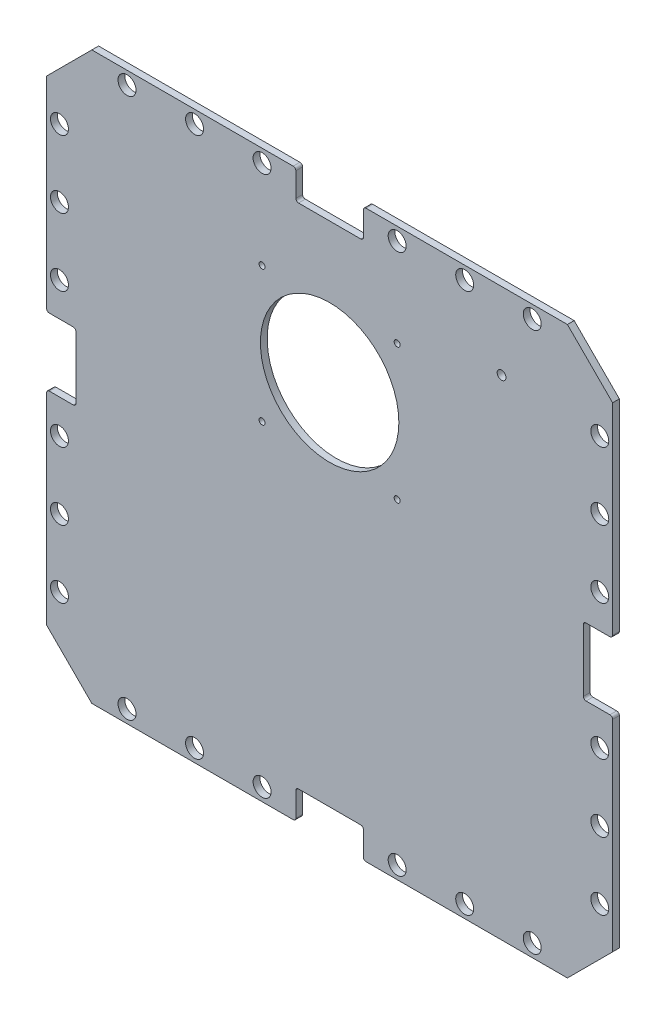
SolidWorks part; units mm, degrees
ref_plane "Front Plane" through (0, 0, 0) normal (0, 0, 1) x (1, 0, 0)
ref_plane "Top Plane" through (0, 0, 0) normal (0, 1, 0) x (1, 0, 0)
ref_plane "Right Plane" through (0, 0, 0) normal (1, 0, 0) x (0, 0, -1)
sketch "Sketch1" plane through (0, 0, 0) normal (0, 0, 1) x (1, 0, 0)
  line L0 (30.226, -4.826) -> (55.626, -4.826) construction
  line L1 (0, 0) -> (212.852, 0)
  line L2 (0, 0) -> (0, -212.852)
  line L3 (0, -212.852) -> (212.852, -212.852)
  line L4 (212.852, 0) -> (212.852, -212.852)
  line L5 (55.626, -4.826) -> (81.026, -4.826) construction
  line L6 (81.026, -4.826) -> (106.426, -4.826) construction
  line L7 (106.426, -4.826) -> (131.826, -4.826) construction
  line L8 (131.826, -4.826) -> (157.226, -4.826) construction
  line L9 (157.226, -4.826) -> (182.626, -4.826) construction
  line L10 (106.426, 0) -> (106.426, -212.852) construction
  line L11 (0, -106.426) -> (212.852, -106.426) construction
  line L12 (16.9978, 0) -> (0, -16.9978)
  line L13 (212.852, -16.9978) -> (195.8542, 0)
  line L14 (195.8542, -212.852) -> (212.852, -195.8542)
  line L15 (0, -195.8542) -> (16.9978, -212.852)
  line L16 (93.726, 0) -> (93.726, -11)
  line L17 (81.026, -38.2041) -> (131.826, -38.2042) construction
  line L18 (81.026, -38.2041) -> (81.026, -89.0042) construction
  line L19 (81.026, -89.0042) -> (131.826, -89.0042) construction
  line L20 (131.826, -38.2042) -> (131.826, -89.0042) construction
  line L21 (106.426, -89.0042) -> (106.426, -38.2041) construction
  line L22 (81.026, -63.6041) -> (131.826, -63.6041) construction
  line L23 (93.726, -11) -> (119.126, -11)
  line L24 (119.126, -11) -> (119.126, 0)
  line L25 (212.852, -93.726) -> (201.852, -93.726)
  line L26 (201.852, -93.726) -> (201.852, -119.126)
  line L27 (201.852, -119.126) -> (212.852, -119.126)
  line L28 (119.126, -212.852) -> (119.126, -201.852)
  line L29 (119.126, -201.852) -> (93.726, -201.852)
  line L30 (93.726, -201.852) -> (93.726, -212.852)
  line L31 (0, -119.126) -> (11, -119.126)
  line L32 (11, -119.126) -> (11, -93.726)
  line L33 (11, -93.726) -> (0, -93.726)
  circle A0 centre (30.226, -4.826) radius 3.38
  circle A1 centre (55.626, -4.826) radius 3.38
  circle A2 centre (81.026, -4.826) radius 3.38
  circle A3 centre (131.826, -4.826) radius 3.38
  circle A4 centre (157.226, -4.826) radius 3.38
  circle A5 centre (182.626, -4.826) radius 3.38
  circle A6 centre (106.426, -4.826) radius 5.1943
  circle A7 centre (208.026, -182.626) radius 3.38
  circle A8 centre (208.026, -157.226) radius 3.38
  circle A9 centre (208.026, -131.826) radius 3.38
  circle A10 centre (208.026, -106.426) radius 5.1943
  circle A11 centre (208.026, -81.026) radius 3.38
  circle A12 centre (208.026, -55.626) radius 3.38
  circle A13 centre (208.026, -30.226) radius 3.38
  circle A14 centre (30.226, -208.026) radius 3.38
  circle A15 centre (55.626, -208.026) radius 3.38
  circle A16 centre (81.026, -208.026) radius 3.38
  circle A17 centre (106.426, -208.026) radius 5.1943
  circle A18 centre (131.826, -208.026) radius 3.38
  circle A19 centre (157.226, -208.026) radius 3.38
  circle A20 centre (182.626, -208.026) radius 3.38
  circle A21 centre (4.826, -30.226) radius 3.38
  circle A22 centre (4.826, -55.626) radius 3.38
  circle A23 centre (4.826, -81.026) radius 3.38
  circle A24 centre (4.826, -106.426) radius 5.1943
  circle A25 centre (4.826, -131.826) radius 3.38
  circle A26 centre (4.826, -157.226) radius 3.38
  circle A27 centre (4.826, -182.626) radius 3.38
  circle A28 centre (106.426, -63.6041) radius 26.035
  circle A29 centre (81.026, -38.2041) radius 1.13
  circle A30 centre (131.826, -38.2042) radius 1.13
  circle A31 centre (131.826, -89.0042) radius 1.13
  circle A32 centre (81.026, -89.0042) radius 1.13
  circle A33 centre (171.0939, -28.8773) radius 1.6631
  point P14 (106.426, -106.426)
  point P69 (106.426, -106.426)
  point P78 (106.426, -106.426)
  point P88 (106.426, -11)
  point P104 (106.426, -106.426)
  dimension "D1" = 6.76
  dimension "D5" = 10.3886
  dimension "D13" = 52.07
  dimension "D14" = 2.26
  dimension "D2" = 30.226
  dimension "D3" = 25.4
  dimension "D4" = 4.826
  dimension "D6" = 212.852
  dimension "D7" = 212.852
  dimension "D9" = 45
  dimension "D10" = 24.0386
  dimension "D12" = 63.6041
  dimension "D15" = 50.8
  dimension "D16" = 25.4
  dimension "D17" = 11
  dimension "D8" = 4
  dimension "D11" = 4
  dimension "D18" = 4
extrude "Boss-Extrude1" add sketch "Sketch1" along normal blind 2.54 contours A24 L2 L3 A17 L4 A10 L1 A6 A27 A26 A25 A23 A22 A21 A20 A19 A18 A16 A15 A14 A13 A12 A11 A9 A8 A7 A5
hole_wizard "#4-40 Tapped Hole1" positions "3DSketch1" profile "Sketch2" tap size "#4-40" standard "ANSI Inch" end condition through all
sketch3d "3DSketch1"
  line L0 (81.026, -38.2041, 2.54) -> (81.026, -38.2041, 0) construction
  line L1 (131.826, -38.2042, 2.54) -> (131.826, -38.2042, 0) construction
  line L2 (131.826, -89.0042, 2.54) -> (131.826, -89.0042, 0) construction
  line L3 (81.026, -89.0042, 2.54) -> (81.026, -89.0042, 0) construction
  point P0 (81.026, -38.2041, 2.54)
  point P4 (131.826, -38.2042, 2.54)
  point P8 (131.826, -89.0042, 2.54)
  point P12 (81.026, -89.0042, 2.54)
sketch "Sketch2" plane through (81.026, -38.2041, 2.54) normal (1, 0, 0) x (0, -1, 0)
  line L0 (0, 0) -> (0, 2.54)
  line L1 (0, 2.54) -> (1.1303, 2.54)
  line L2 (1.1303, 2.54) -> (1.1303, 0)
  line L5 (1.1303, 0) -> (0, 0)
  line L11 (0, -6.35) -> (0, 107.95) construction
  dimension "Thru Tap Drill Dia." = 2.2606
  dimension "Thru Tap Drill Depth" = 2.54
cosmetic thread "Hole Thread1" parameters "D2"=2.8448
cosmetic thread "Hole Thread2" parameters "D2"=2.8448
cosmetic thread "Hole Thread3" parameters "D2"=2.8448
cosmetic thread "Hole Thread4" parameters "D2"=2.8448
fillet "Fillet1" radius 1 16 edges at (0, -93.726, 1.27) (11, -93.726, 1.27) (0, -119.126, 1.27) (11, -119.126, 1.27) (93.726, -212.852, 1.27) (93.726, -201.852, 1.27) (119.126, -212.852, 1.27) (119.126, -201.852, 1.27) (212.852, -119.126, 1.27) (201.852, -119.126, 1.27) (212.852, -93.726, 1.27) (201.852, -93.726, 1.27) (119.126, -11, 1.27) (119.126, 0, 1.27) (93.726, -11, 1.27) (93.726, 0, 1.27)
